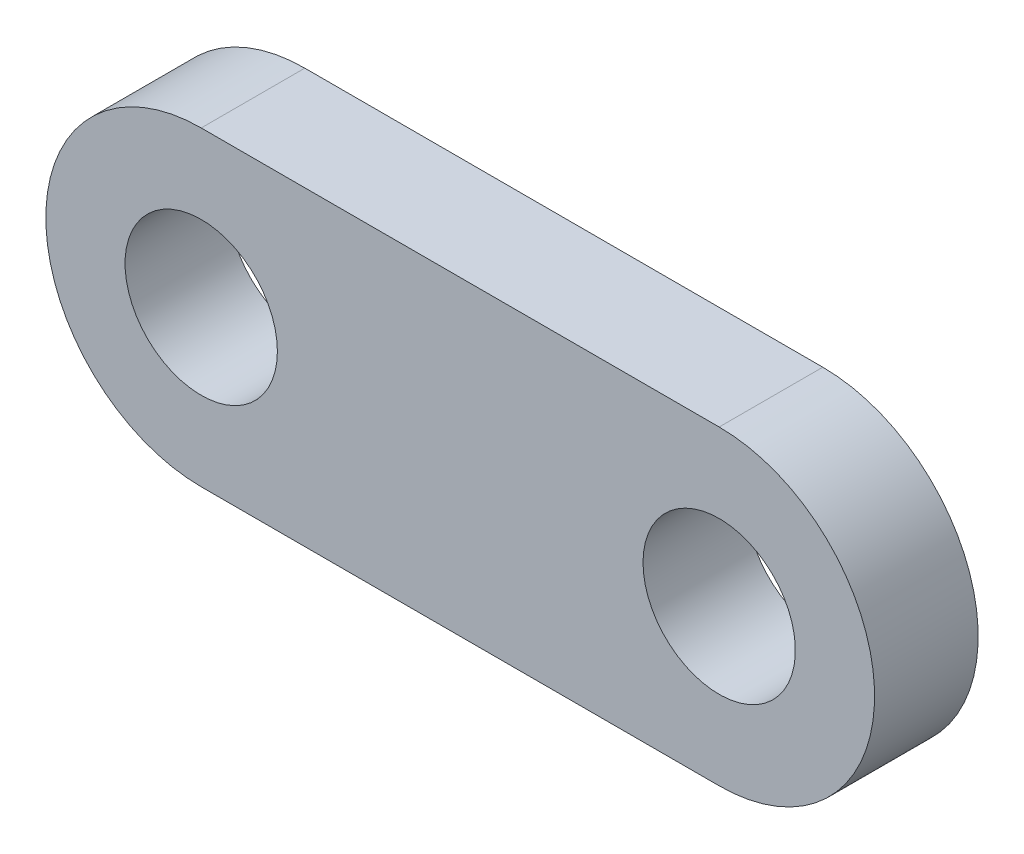
SolidWorks part; units mm, degrees
ref_plane "Front Plane" through (0, 0, 0) normal (0, 0, 1) x (1, 0, 0)
ref_plane "Top Plane" through (0, 0, 0) normal (0, 1, 0) x (1, 0, 0)
ref_plane "Right Plane" through (0, 0, 0) normal (1, 0, 0) x (0, 0, -1)
sketch "Sketch1" plane through (0, 0, 0) normal (0, 0, 1) x (1, 0, 0)
  line L0 (-25, 0) -> (25, 0)
  line L1 (25, 0) -> (25, -30)
  line L2 (25, -30) -> (-25, -30)
  line L3 (-25, -30) -> (-25, 0)
  point P3 (0, 0)
  dimension "D1" = 50
  dimension "D2" = 30
extrude "Boss-Extrude2" add sketch "Sketch1" along normal blind 10
sketch "Sketch4" plane through (0, 0, 10) normal (0, 0, 1) x (1, 0, 0)
  line L0 (25, -30) -> (25, 0) construction
  line L1 (25, 0) -> (25, -30)
  arc A0 (25, -30) -> (25, 0) centre (25, -15) ccw
extrude "Boss-Extrude3" add sketch "Sketch4" against normal blind 10
sketch "Sketch5" plane through (0, 0, 10) normal (0, 0, 1) x (1, 0, 0)
  line L0 (-25, 0) -> (-25, -30) construction
  line L1 (-25, 0) -> (-25, -30)
  arc A0 (-25, 0) -> (-25, -30) centre (-25, -15) ccw
extrude "Boss-Extrude4" add sketch "Sketch5" against normal blind 10
sketch "Sketch6" plane through (0, 0, 10) normal (0, 0, 1) x (1, 0, 0)
  line L0 (0, 29.1309) -> (0, -67.8294) construction
  circle A0 centre (-25, -15) radius 7.3535
  arc A2 (-25, 0) -> (-25, -30) centre (-25, -15) ccw construction
  circle A4 centre (25, -15) radius 7.3535
  point P8 (-40, -15)
  dimension "D2" = 15
  dimension "D1" = 15
extrude "Cut-Extrude1" cut sketch "Sketch6" against normal blind 10
